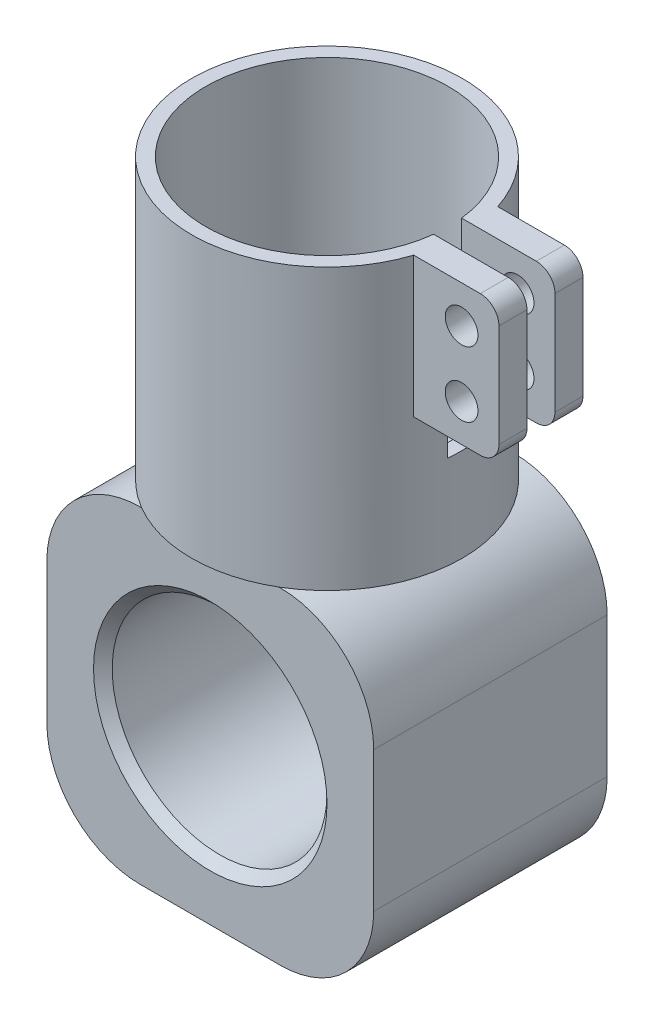
SolidWorks part; units mm, degrees
ref_plane "Front Plane" through (0, 0, 0) normal (0, 0, 1) x (1, 0, 0)
ref_plane "Top Plane" through (0, 0, 0) normal (0, 1, 0) x (1, 0, 0)
ref_plane "Right Plane" through (0, 0, 0) normal (1, 0, 0) x (0, 0, -1)
sketch "Sketch2" plane through (0, 0, 0) normal (0, 0, 1) x (1, 0, 0)
  line L1 (-7.5, 17.5) -> (7.5, 17.5)
  line L2 (-17.5, 7.5) -> (-17.5, -7.5)
  line L3 (-7.5, -17.5) -> (7.5, -17.5)
  line L4 (17.5, 7.5) -> (17.5, -7.5)
  line L5 (-17.5, 17.5) -> (17.5, -17.5) construction
  line L6 (-17.5, -17.5) -> (17.5, 17.5) construction
  circle A0 centre (0, 0) radius 11.5
  arc A1 (7.5, -17.5) -> (17.5, -7.5) centre (7.5, -7.5) ccw
  arc A2 (-17.5, -7.5) -> (-7.5, -17.5) centre (-7.5, -7.5) ccw
  arc A3 (7.5, 17.5) -> (17.5, 7.5) centre (7.5, 7.5) cw
  arc A4 (-7.5, 17.5) -> (-17.5, 7.5) centre (-7.5, 7.5) ccw
  dimension "D3" = 23
  dimension "D4" = 10
  dimension "D1" = 35
  dimension "D2" = 35
extrude "Boss-Extrude1" add sketch "Sketch2" along normal mid plane 25
sketch "Sketch4" plane through (0, 17.5, 0) normal (0, 1, 0) x (1, 0, 0)
  circle A0 centre (0, 0) radius 13
  dimension "D1" = 26
extrude "Extrude-Thin1" add sketch "Sketch4" along normal blind 30 thin
sketch "Sketch5" plane through (0, 0, 0) normal (0, 0, 1) x (1, 0, 0)
  line L0 (14.5, 47.5) -> (-14.5, 47.5) construction
  line L1 (9.2204, 47.5) -> (21.6805, 47.5)
  line L2 (9.2204, 47.5) -> (9.2204, 27.5)
  line L3 (9.2204, 27.5) -> (21.6805, 27.5)
  line L4 (21.6805, 47.5) -> (21.6805, 27.5)
  dimension "D1" = 20
extrude "Cut-Extrude1" cut sketch "Sketch5" against normal mid plane 3
sketch "Sketch8" plane through (0, 0, 1.5) normal (0, 0, -1) x (-1, 0, 0)
  line L0 (-12.9132, 27.5) -> (-12.9132, 47.5) construction
  line L1 (-12.9132, 47.5) -> (-20.9132, 47.5)
  line L2 (-12.9132, 47.5) -> (-12.9132, 32.5)
  line L3 (-12.9132, 32.5) -> (-20.9132, 32.5)
  line L4 (-22.9132, 45.5) -> (-22.9132, 34.5)
  line L5 (-14.4222, 47.5) -> (-12.9132, 47.5) construction
  arc A0 (-20.9132, 32.5) -> (-22.9132, 34.5) centre (-20.9132, 34.5) cw
  arc A1 (-20.9132, 47.5) -> (-22.9132, 45.5) centre (-20.9132, 45.5) ccw
  circle A2 centre (-18.9132, 43.5) radius 1.75
  circle A3 centre (-18.9132, 36.5) radius 1.75
  point P10 (-22.9132, 32.5)
  point P13 (-22.9132, 47.5)
  point P18 (0, 0)
  dimension "D3" = 2
  dimension "D7" = 3.5
  dimension "D8" = 3.5
  dimension "D1" = 10
  dimension "D2" = 15
  dimension "D4" = 4
  dimension "D5" = 7
  dimension "D6" = 6
extrude "Boss-Extrude2" add sketch "Sketch8" against normal blind 3
mirror "Mirror1" about plane through (0, 0, 0) normal (0, 0, 1) of "Boss-Extrude2"
chamfer "Chamfer1" distance 1 angle 45 2 edges at (11.5, 0, 12.5) (11.5, 0, -12.5)
